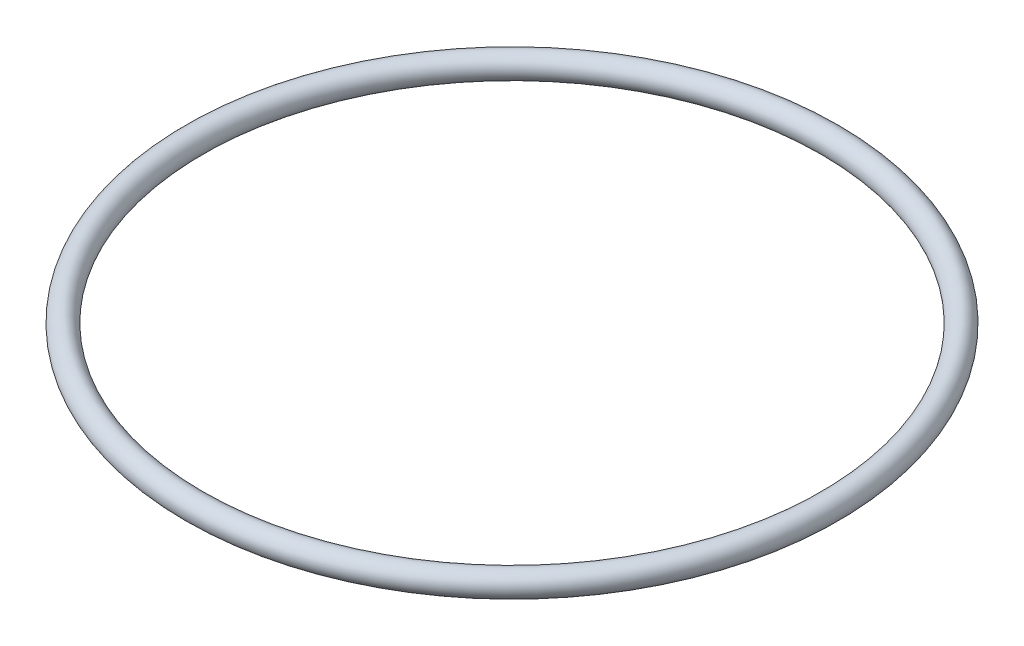
SolidWorks part; units mm, degrees
ref_plane "Alzado" through (0, 0, 0) normal (0, 0, 1) x (1, 0, 0)
ref_plane "Planta" through (0, 0, 0) normal (0, 1, 0) x (1, 0, 0)
ref_plane "Vista lateral" through (0, 0, 0) normal (1, 0, 0) x (0, 0, -1)
sketch "Croquis1" plane through (0, 0, 0) normal (0, 0, 1) x (1, 0, 0)
  line L0 (0, 0) -> (33.15, 0) construction
  line L1 (0, 0) -> (0, 11.4953) construction
  circle A0 centre (33.15, 0) radius 1.25
  dimension "D1" = 2.5
  dimension "D2" = 33.15
revolve "Revolución1" add sketch "Croquis1" angle 360 about L1
